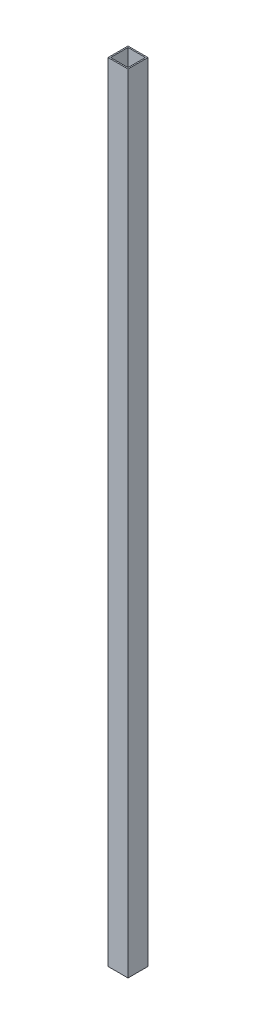
SolidWorks part; units mm, degrees
material "6061 Alloy"
ref_plane "Front Plane" through (0, 0, 0) normal (0, 0, 1) x (1, 0, 0)
ref_plane "Top Plane" through (0, 0, 0) normal (0, 1, 0) x (1, 0, 0)
ref_plane "Right Plane" through (0, 0, 0) normal (1, 0, 0) x (0, 0, -1)
sketch "Sketch1" plane through (0, 0, 0) normal (0, 1, 0) x (1, 0, 0)
  line L1 (12.7, -12.7) -> (-12.7, -12.7)
  line L2 (12.7, -12.7) -> (12.7, 12.7)
  line L3 (12.7, 12.7) -> (-12.7, 12.7)
  line L4 (-12.7, -12.7) -> (-12.7, 12.7)
  line L5 (12.7, -12.7) -> (-12.7, 12.7) construction
  line L6 (12.7, 12.7) -> (-12.7, -12.7) construction
  line L7 (11.1125, -11.1125) -> (-11.1125, -11.1125)
  line L8 (11.1125, -11.1125) -> (11.1125, 11.1125)
  line L9 (11.1125, 11.1125) -> (-11.1125, 11.1125)
  line L10 (-11.1125, -11.1125) -> (-11.1125, 11.1125)
  line L11 (11.1125, -11.1125) -> (-11.1125, 11.1125) construction
  line L12 (11.1125, 11.1125) -> (-11.1125, -11.1125) construction
  point P0 (0, 0)
  point P6 (0, 0)
  dimension "D1" = 25.4
  dimension "D2" = 25.4
  dimension "D3" = 1.5875
extrude "Boss-Extrude2" add sketch "Sketch1" along normal blind 1003.3
